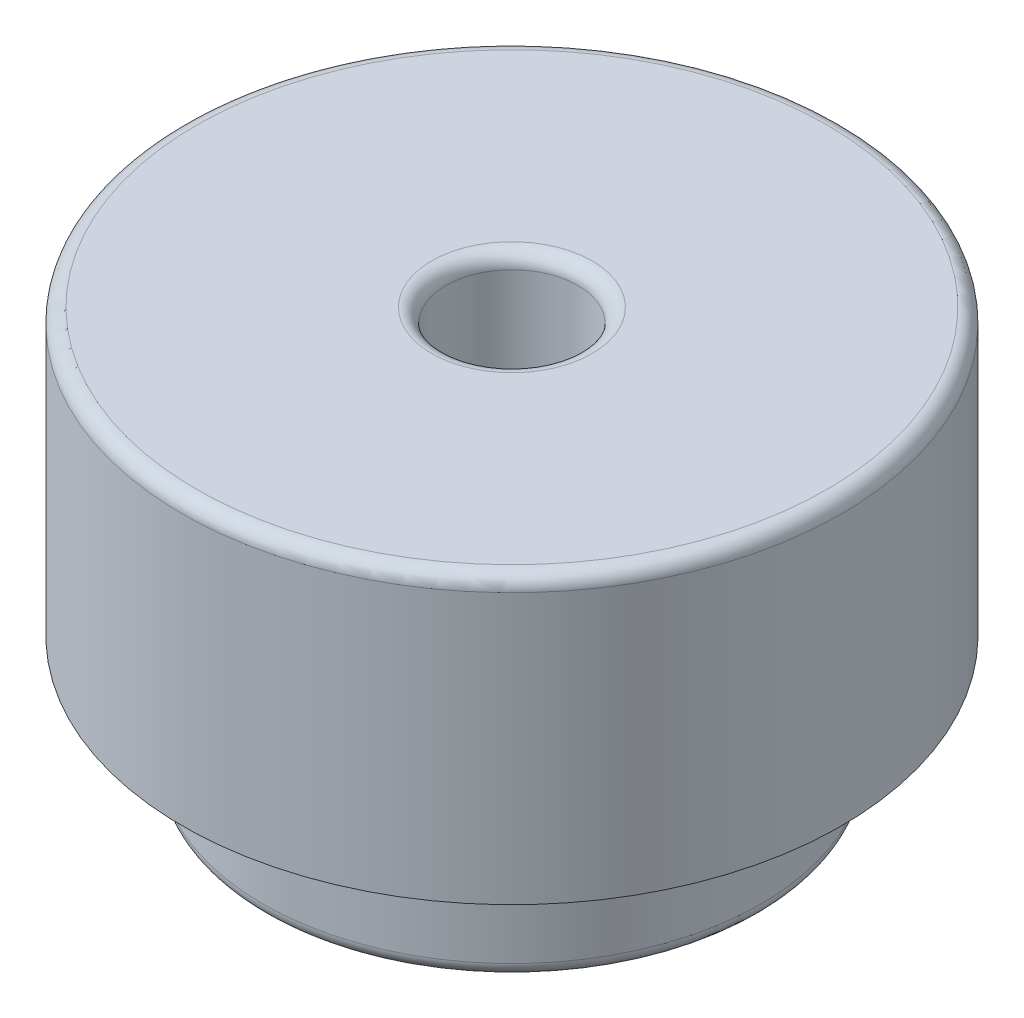
SolidWorks part; units mm, degrees
ref_plane "Front Plane" through (0, 0, 0) normal (0, 0, 1) x (1, 0, 0)
ref_plane "Top Plane" through (0, 0, 0) normal (0, 1, 0) x (1, 0, 0)
ref_plane "Right Plane" through (0, 0, 0) normal (1, 0, 0) x (0, 0, -1)
sketch "Sketch1" plane through (0, 0, 0) normal (0, 0, 1) x (1, 0, 0)
  line L0 (0, 0) -> (0, 21.1429) construction
  line L1 (4.9101, -8.0333) -> (4.9101, 20.0857)
  line L2 (4.9101, 21.1429) -> (128.348, 21.1429) construction
  line L3 (4.9101, 21.1429) -> (4.9101, 0) construction
  line L4 (4.9101, 0) -> (32.0899, 0) construction
  line L6 (5.9672, 21.1429) -> (23.4429, 21.1429)
  line L8 (5.9672, -9.0905) -> (17.4429, -9.0905)
  line L9 (18.5, -8.0333) -> (18.5, -0.4411)
  line L12 (24.5, 20.0857) -> (24.5, 0)
  line L13 (18.9411, 0) -> (24.5, 0)
  arc A0 (4.9101, -8.0333) -> (5.9672, -9.0905) centre (5.9672, -8.0333) ccw
  arc A1 (17.4429, -9.0905) -> (18.5, -8.0333) centre (17.4429, -8.0333) ccw
  arc A3 (4.9101, 20.0857) -> (5.9672, 21.1429) centre (5.9672, 20.0857) cw
  arc A4 (23.4429, 21.1429) -> (24.5, 20.0857) centre (23.4429, 20.0857) cw
  arc A5 (18.5, -0.4411) -> (18.9411, 0) centre (18.9411, -0.4411) cw
  point P18 (18.5, 0)
  point P27 (18.5, 0)
  dimension "D7" = 1.0571
  dimension "D6" = 0.4411
  dimension "D1" = 21.1429
  dimension "D2" = 4.9101
  dimension "D5" = 9.0905
  dimension "D3" = 19.5899
  dimension "D4" = 13.5899
revolve "Revolve1" add sketch "Sketch1" angle 360 about L0
equation "\"D1@Sketch1\"=\"Upper_Mount_largest_radius\"/0.875"
equation "\"D2@Sketch1\"=\"Lower_Mount_piston_rod_radius\""
equation "\"D5@Sketch1\"=(\"Upper_Mount_largest_radius\"/1.90909091)-0.6mm"
equation "\"Lower_Mount_piston_rod_radius\"\t=4.9101"
equation "\"Upper_Mount_largest_radius\" =18.5"
equation "\"D3@Sketch1\"=(((2*\"Upper_Mount_largest_radius\")+(\"Upper_mount_wall_thickness\"))/2)-(\"Lower_Mount_piston_rod_radius\")"
equation "\"D4@Sketch1\"=\"Upper_Mount_largest_radius\"-\"Lower_Mount_piston_rod_radius\""
equation "\"D7@Sketch1\"=\"Upper_Mount_largest_radius\"/17.5"
equation "\"Upper_mount_wall_thickness\" =12"
equation "\"Lower_Mount_piston_rod_length\" =149"
equation "\"Piston_orifice_dia\"=0.47773"
equation "\"Spring_inner_dia\" =80"
equation "\"Spring_wire_dia\" =8"
equation "\"D6@Sketch1\"=((((2*\"Upper_Mount_largest_radius\")+(\"Upper_mount_wall_thickness\"))/2)-(\"Lower_Mount_piston_rod_radius\")-1mm)/42.14"
